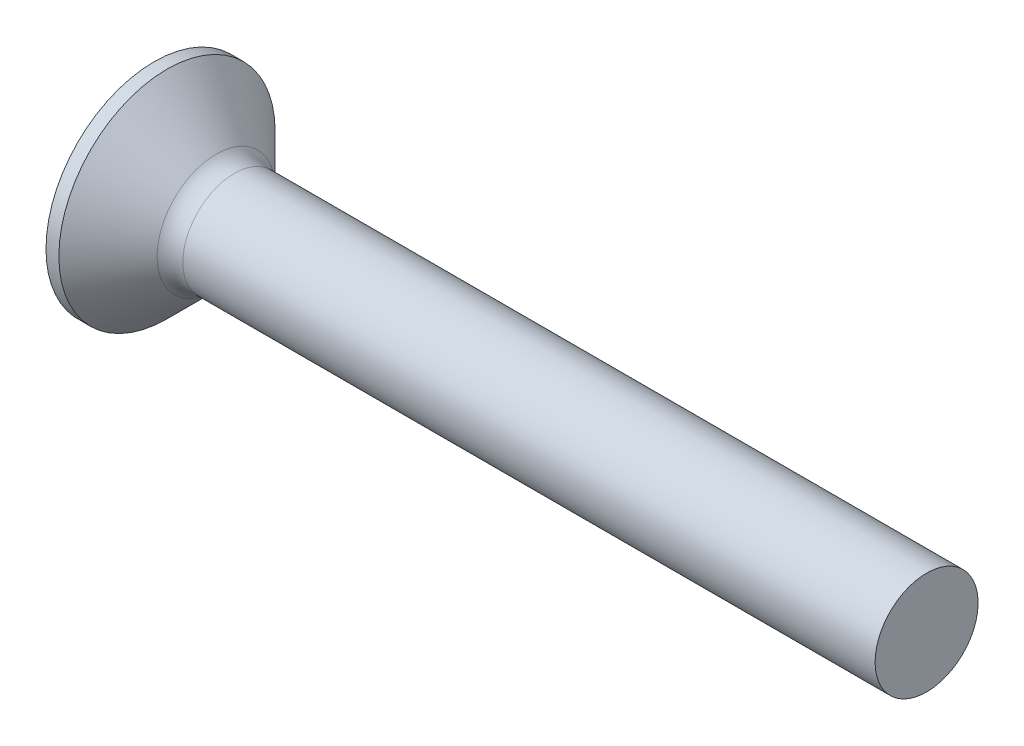
SolidWorks part; units mm, degrees
ref_plane "Plane1" through (0, 0, 0) normal (0, 0, 1) x (1, 0, 0)
ref_plane "Plane2" through (0, 0, 0) normal (0, 1, 0) x (1, 0, 0)
ref_plane "Plane3" through (0, 0, 0) normal (1, 0, 0) x (0, 0, -1)
other "Configuration Table"
sketch "BodySke" plane through (0, 0, 0) normal (0, 0, 1) x (1, 0, 0)
  line L0 (0, 0) -> (31, 0)
  line L1 (31, 0) -> (31, 2)
  line L2 (31, 2) -> (3.7, 2)
  line L3 (1.5, -4.2) -> (3.7, -2) construction
  line L4 (-15.875, 0) -> (82.55, 0) construction
  line L5 (1.5, 4.2) -> (3.7, 2)
  line L6 (4.4, 5.175) -> (4.4, -10.7) construction
  line L7 (1, 2.7793) -> (1, -13.0957) construction
  line L8 (1.5, 4.2) -> (1, 4.2)
  arc A0 (0, 0) -> (1, 4.2) centre (9.32, 0) cw
  dimension "Head_ang" = 90
  dimension "Diameter" = 4
  dimension "Advance" = 0.7
  dimension "Thread_nom" = 30
  dimension "Oval_ht" = 1
  dimension "Side_ht" = 2.7
  dimension "Head_dia" = 8.4
  dimension "Length" = 30
revolve "Base-Revolve" add sketch "BodySke" angle 360 about L4
cosmetic thread "ThreadCosmetic" parameters "Thread_length"=26.6, "Thread_minor"=3.22
fillet "Fillet1" radius 1 1 edges at (3.7, 0, 2)
sketch "Sketch3" plane through (0, 0, 0) normal (1, 0, 0) x (0, 0, -1)
  line L0 (0.515, -2.5) -> (-0.515, -2.5)
  line L1 (0.515, -2.5) -> (0.515, 2.5)
  line L2 (-0.515, 2.5) -> (0.515, 2.5)
  line L3 (-0.515, 2.5) -> (-0.515, -2.5)
  dimension "Cross_width" = 1.03
  dimension "D1" = 0.515
  dimension "Cross_dia" = 5
  dimension "D2" = 2.5
ref_plane "Plane4" through (3.1, 0, 0) normal (1, 0, 0) x (0, 0, -1)
sketch "Sketch4" plane through (3.1, 0, 0) normal (1, 0, 0) x (0, 0, -1)
  line L0 (0.515, -0.9544) -> (-0.515, -0.9544)
  line L1 (0.515, -0.9544) -> (0.515, 0.9544)
  line L2 (-0.515, 0.9544) -> (0.515, 0.9544)
  line L3 (-0.515, 0.9544) -> (-0.515, -0.9544)
  dimension "D1" = 1.03
  dimension "D2" = 1.9088
  dimension "D3" = 0.515
  dimension "D4" = 0.9544
loft "Recess" cut profiles "Sketch3", "Sketch4"
pattern_circular "RecPat" count 2 every 90 about axis through (0, 0, 0) along (1, 0, 0) of "Recess"
sketch "RecCorSke" plane through (0, 0, 0) normal (0, 0, 1) x (1, 0, 0)
  line L0 (-3.175, 0) -> (15.875, 0) construction
  line L2 (0, 0) -> (0, 1.0678)
  line L3 (0, 1.0678) -> (3.1, 0.851)
  line L4 (3.1, 0.851) -> (3.3765, 0)
  line L5 (3.3765, 0) -> (0, 0)
  dimension "Diameter" = 1.702
  dimension "Depth" = 3.1
  dimension "Draft_angle" = 4
  dimension "Bottom_angle" = 18
revolve "RecessCore" cut sketch "RecCorSke" angle 360 about L0
sketch "ThdSchSke" plane through (0, 0, 0) normal (0, 0, 1) x (1, 0, 0)
  line L0 (4.4, -1.61) -> (4.1269, -2)
  line L1 (4.4, -1.61) -> (4.6731, -2)
  line L2 (4.6731, -2) -> (4.6731, -2.5)
  line L3 (-3.175, 0) -> (5.1513, 0) construction
  line L5 (4.6731, -2.5) -> (4.1269, -2.5)
  line L6 (4.1269, -2.5) -> (4.1269, -2)
  dimension "Diameter" = 4
  dimension "SideAngle" = 55
  dimension "VeeAngle" = 70
  dimension "Thread_minor" = 3.22
  dimension "Overcut" = 5
  dimension "Start" = 4.4
revolve "ThreadSchematic" [suppressed] cut sketch "ThdSchSke" angle 360 about L3
pattern_linear "ThdSchPat" [suppressed]
equation "\"D1@Sketch3\" = \"Cross_width@Sketch3\" / 2"
equation "\"D2@Sketch3\" = \"Cross_dia@Sketch3\" / 2"
equation "\"Depth@RecCorSke\" = \"Cross_depth@Plane4\""
equation "\"D1@Sketch4\" = \"Cross_width@Sketch3\""
equation "\"D2@Sketch4\" = \"Cross_dia@Sketch3\" - 2.0 * \"Cross_depth@Plane4\" * tan(26.5  * 0.017453292)"
equation "\"D3@Sketch4\" = \"D1@Sketch4\" / 2"
equation "\"D4@Sketch4\" = \"D2@Sketch4\" / 2"
equation "\"Thread_length@ThreadCosmetic\" = ((sgn( (\"Length@BodySke\" - \"Advance@BodySke\" - \"Side_ht@BodySke\" ) - \"Thread_nom@BodySke\" )-1)*( (\"Length@BodySke\" - \"Advance@BodySke\" - \"Side_ht@BodySke\" ) - \"Thread_nom@BodySke\" ))/-2+ \"Thread_nom@BodySke\""
equation "\"Thread_minor@ThdSchSke\" = \"Thread_minor@ThreadCosmetic\""
equation "\"Diameter@ThdSchSke\" = \"Diameter@BodySke\""
equation "\"Overcut@ThdSchSke\" = \"Diameter@BodySke\" * 1.25"
equation "\"Start@ThdSchSke\" = \"Oval_ht@BodySke\" + \"Length@BodySke\" - \"Thread_length@ThreadCosmetic\"  '---Countersunk---"
equation "\"Num_threads@ThdSchPat\" = int( \"Thread_length@ThreadCosmetic\" / \"Advance@BodySke\" + 0.999 )  + 1"
equation "\"Advance@ThdSchPat\" = \"Thread_length@ThreadCosmetic\" /  (\"Num_threads@ThdSchPat\" - 1) 'relax it"
